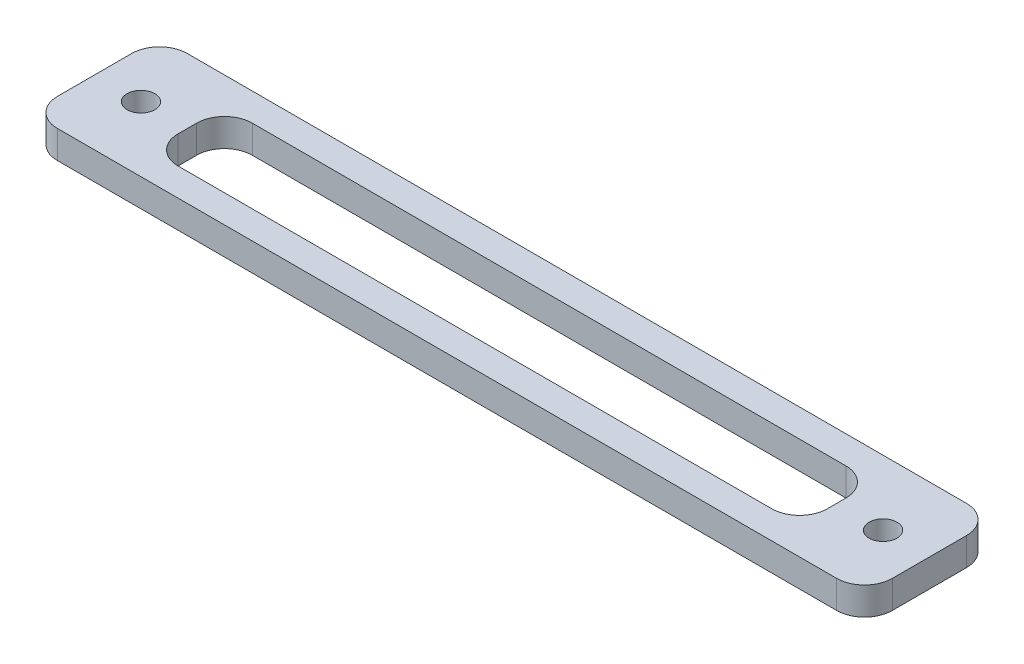
SolidWorks part; units mm, degrees
material "Thornel Mat VMA"
ref_plane "前视基准面" through (0, 0, 0) normal (0, 0, 1) x (1, 0, 0)
ref_plane "上视基准面" through (0, 0, 0) normal (0, 1, 0) x (1, 0, 0)
ref_plane "右视基准面" through (0, 0, 0) normal (1, 0, 0) x (0, 0, -1)
other "Configuration Table"
sketch "草图1" plane through (0, 0, 0) normal (0, 1, 0) x (1, 0, 0)
  line L0 (0, 0) -> (0, 91.7067) construction
  line L1 (-45, -7) -> (45, -7)
  line L2 (-45, -7) -> (-45, 7)
  line L3 (-45, 7) -> (45, 7)
  line L4 (45, -7) -> (45, 7)
  line L5 (-45, -7) -> (45, 7) construction
  line L6 (-45, 7) -> (45, -7) construction
  line L7 (-35, -4) -> (35, -4)
  line L8 (-35, -4) -> (-35, 4)
  line L9 (-35, 4) -> (35, 4)
  line L10 (35, -4) -> (35, 4)
  line L11 (-35, -4) -> (35, 4) construction
  line L12 (-35, 4) -> (35, -4) construction
  circle A0 centre (-40, 0) radius 1.5
  circle A1 centre (40, 0) radius 1.5
  point P0 (0, 0)
  point P6 (0, 0)
  dimension "D2" = 80
  dimension "D4" = 3
  dimension "D7" = 7
  dimension "D1" = 90
  dimension "D3" = 14
  dimension "D5" = 70
  dimension "D6" = 8
extrude "凸台-拉伸1" add sketch "草图1" along normal blind 3
fillet "圆角1" radius 3 8 edges at (-45, 1.5, 7) (-45, 1.5, -7) (45, 1.5, 7) (45, 1.5, -7) (35, 1.5, 4) (35, 1.5, -4) (-35, 1.5, 4) (-35, 1.5, -4)
